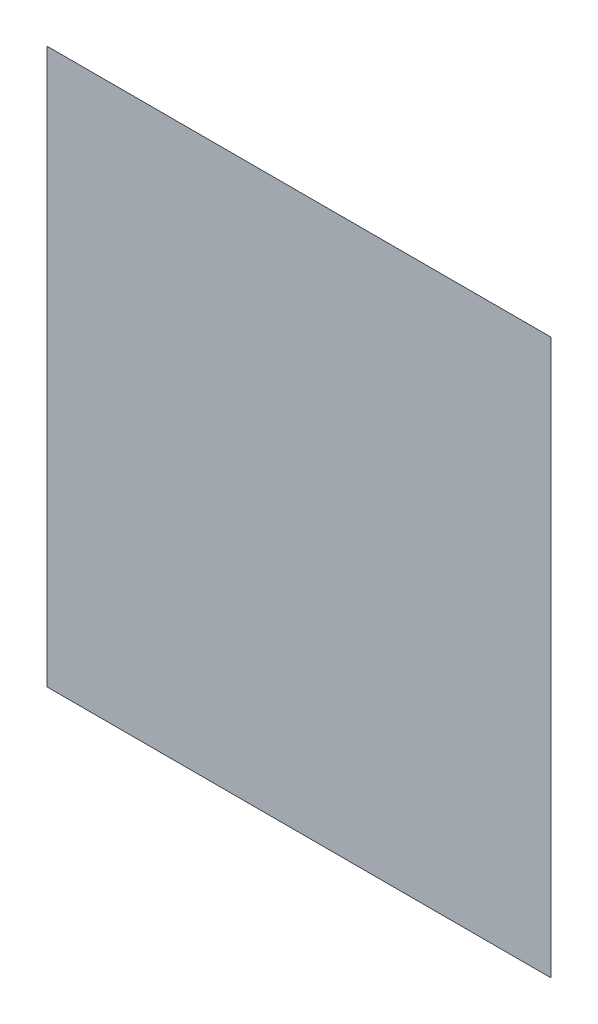
SolidWorks part; units mm, degrees
material "A-Glass Fiber"
ref_plane "Front" through (0, 0, 0) normal (0, 0, 1) x (1, 0, 0)
ref_plane "Top" through (0, 0, 0) normal (0, 1, 0) x (1, 0, 0)
ref_plane "Right" through (0, 0, 0) normal (1, 0, 0) x (0, 0, -1)
sketch "Sketch1" plane through (0, 0, 0) normal (0, 0, 1) x (1, 0, 0)
  line L0 (-22.2418, 0) -> (39.1648, 0) construction
  line L1 (0, 39.7692) -> (0, -29.6154) construction
  line L2 (-10, -11) -> (10, -11)
  line L3 (10, -11) -> (10, 11)
  line L4 (10, 11) -> (-10, 11)
  line L5 (-10, 11) -> (-10, -11)
  point P7 (0, 0)
  point P10 (0, 0)
  point P11 (0, 0)
  point P12 (0, 0)
  point P13 (0, 0)
  point P16 (0, -17.2857)
  dimension "D1" = 11
  dimension "D2" = 22
  dimension "D3" = 0
  dimension "D4" = 10
  dimension "D5" = 10
extrude "Boss-Extrude1" add sketch "Sketch1" along normal blind 0.0001
